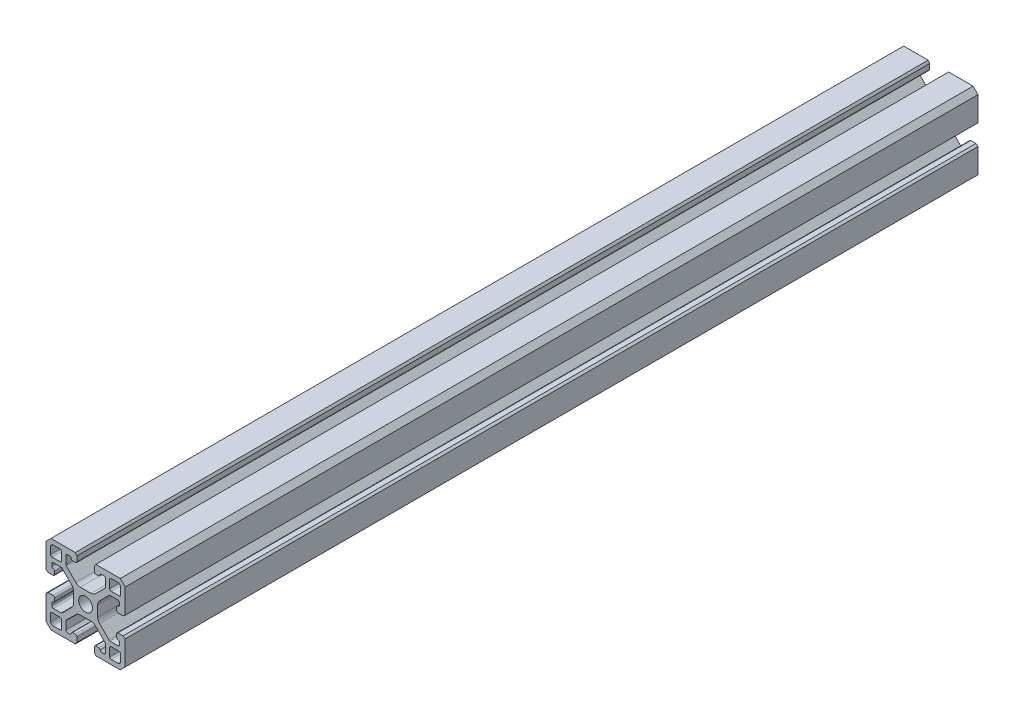
SolidWorks part; units mm, degrees
material "6063-T6"
ref_plane "Front Plane" through (0, 0, 0) normal (0, 0, 1) x (1, 0, 0)
ref_plane "Top Plane" through (0, 0, 0) normal (0, 1, 0) x (1, 0, 0)
ref_plane "Right Plane" through (0, 0, 0) normal (1, 0, 0) x (0, 0, -1)
sketch "Sketch1" plane through (0, 0, 0) normal (0, 0, 1) x (-1, 0, 0)
  line L0 (19.05, 0) -> (-19.05, 0) construction
  line L1 (0, -19.05) -> (0, 19.05) construction
  line L2 (-19.05, 4.9276) -> (-19.05, 16.6878)
  line L3 (-18.044, 4.1656) -> (-19.05, 4.9276)
  line L4 (-15.6692, 4.1656) -> (-18.044, 4.1656)
  line L5 (-14.9297, 6.2238) -> (-14.9074, 4.9409)
  line L6 (-16.256, 8.763) -> (-16.256, 7.7216)
  line L7 (-16.256, -7.7216) -> (-16.256, -8.763)
  line L8 (-14.9074, -4.9409) -> (-14.9297, -6.2238)
  line L9 (-18.044, -4.1656) -> (-15.6692, -4.1656)
  line L10 (-19.05, -4.9276) -> (-18.044, -4.1656)
  line L11 (-19.05, -16.6878) -> (-19.05, -4.9276)
  line L26 (-16.8656, 12.319) -> (-16.8656, 15.6829)
  line L27 (-16.6424, 16.2217) -> (-16.2217, 16.6424)
  line L28 (-15.6829, 16.8656) -> (-12.319, 16.8656)
  line L29 (-11.557, 16.1036) -> (-11.557, 12.319)
  line L30 (-12.319, 11.557) -> (-16.1036, 11.557)
  line L31 (-6.7001, -4.7245) -> (-11.2775, -9.3018)
  line L32 (-11.8163, -9.525) -> (-15.494, -9.525)
  line L34 (-15.494, 9.525) -> (-11.8163, 9.525)
  line L35 (-11.2775, 9.3018) -> (-6.7001, 4.7245)
  line L36 (-5.8074, 2.5692) -> (-5.8074, -2.5692)
  line L37 (-16.1036, -11.557) -> (-12.319, -11.557)
  line L38 (-11.557, -12.319) -> (-11.557, -16.1036)
  line L39 (-12.319, -16.8656) -> (-15.6829, -16.8656)
  line L40 (-16.2217, -16.6424) -> (-16.6424, -16.2217)
  line L41 (-16.8656, -15.6829) -> (-16.8656, -12.319)
  line L42 (15.6829, -16.8656) -> (12.319, -16.8656)
  line L43 (11.557, -16.1036) -> (11.557, -12.319)
  line L44 (12.319, -11.557) -> (16.1036, -11.557)
  line L45 (16.8656, -12.319) -> (16.8656, -15.6829)
  line L46 (16.6424, -16.2217) -> (16.2217, -16.6424)
  line L47 (11.557, 12.319) -> (11.557, 16.1036)
  line L48 (12.319, 16.8656) -> (15.6829, 16.8656)
  line L49 (16.2217, 16.6424) -> (16.6424, 16.2217)
  line L100 (5.8074, -2.5692) -> (5.8074, 2.5692)
  line L101 (6.7001, 4.7245) -> (11.2775, 9.3018)
  line L102 (11.8163, 9.525) -> (15.494, 9.525)
  line L103 (16.256, 8.763) -> (16.256, 7.7216)
  line L104 (14.9297, 6.2238) -> (14.9074, 4.9409)
  line L105 (15.6692, 4.1656) -> (18.044, 4.1656)
  line L106 (18.044, 4.1656) -> (19.05, 4.9276)
  line L107 (19.05, 4.9276) -> (19.05, 16.6878)
  line L108 (19.05, 16.6878) -> (16.6878, 19.05)
  line L109 (16.6878, 19.05) -> (4.9276, 19.05)
  line L110 (4.9276, 19.05) -> (4.1656, 18.044)
  line L111 (4.1656, 18.044) -> (4.1656, 15.6692)
  line L112 (4.9409, 14.9074) -> (6.2238, 14.9297)
  line L113 (7.7216, 16.256) -> (8.763, 16.256)
  line L114 (9.525, 15.494) -> (9.525, 11.8163)
  line L115 (9.3018, 11.2775) -> (4.7245, 6.7001)
  line L116 (2.5692, 5.8074) -> (-2.5692, 5.8074)
  line L117 (-4.7245, 6.7001) -> (-9.3018, 11.2775)
  line L118 (-9.525, 11.8163) -> (-9.525, 15.494)
  line L119 (-8.763, 16.256) -> (-7.7216, 16.256)
  line L120 (-6.2238, 14.9297) -> (-4.9409, 14.9074)
  line L121 (-4.1656, 15.6692) -> (-4.1656, 18.044)
  line L122 (-4.1656, 18.044) -> (-4.9276, 19.05)
  line L123 (-4.9276, 19.05) -> (-16.6878, 19.05)
  line L124 (-16.6878, 19.05) -> (-19.05, 16.6878)
  line L126 (-19.05, -16.6878) -> (-16.6878, -19.05)
  line L127 (-16.6878, -19.05) -> (-4.9276, -19.05)
  line L128 (-4.9276, -19.05) -> (-4.1656, -18.044)
  line L129 (-4.1656, -18.044) -> (-4.1656, -15.6692)
  line L130 (-4.9409, -14.9074) -> (-6.2238, -14.9297)
  line L131 (-7.7216, -16.256) -> (-8.763, -16.256)
  line L132 (-9.525, -15.494) -> (-9.525, -11.8163)
  line L133 (-9.3018, -11.2775) -> (-4.7245, -6.7001)
  line L134 (-2.5692, -5.8074) -> (2.5692, -5.8074)
  line L135 (4.7245, -6.7001) -> (9.3018, -11.2775)
  line L136 (9.525, -11.8163) -> (9.525, -15.494)
  line L137 (8.763, -16.256) -> (7.7216, -16.256)
  line L138 (6.2238, -14.9297) -> (4.9409, -14.9074)
  line L139 (4.1656, -15.6692) -> (4.1656, -18.044)
  line L140 (4.1656, -18.044) -> (4.9409, -19.05)
  line L141 (4.9409, -19.05) -> (16.6878, -19.05)
  line L142 (16.6878, -19.05) -> (19.05, -16.6878)
  line L143 (19.05, -16.6878) -> (19.05, -4.9276)
  line L144 (19.05, -4.9276) -> (18.044, -4.1656)
  line L145 (18.044, -4.1656) -> (15.6692, -4.1656)
  line L146 (14.9074, -4.9409) -> (14.9297, -6.2238)
  line L147 (16.256, -7.7216) -> (16.256, -8.763)
  line L148 (15.494, -9.525) -> (11.8163, -9.525)
  line L149 (11.2775, -9.3018) -> (6.7001, -4.7245)
  line L150 (16.8656, 15.6829) -> (16.8656, 12.319)
  line L151 (16.1036, 11.557) -> (12.319, 11.557)
  arc A0 (-16.256, 8.763) -> (-15.494, 9.525) centre (-15.494, 8.763) cw
  arc A1 (-14.9074, 4.9409) -> (-15.6692, 4.1656) centre (-15.6692, 4.9276) cw
  arc A2 (-15.5928, 6.966) -> (-14.9297, 6.2238) centre (-15.6916, 6.2105) cw
  arc A3 (-15.5928, 6.966) -> (-16.256, 7.7216) centre (-15.494, 7.7216) cw
  arc A4 (-15.494, -9.525) -> (-16.256, -8.763) centre (-15.494, -8.763) cw
  arc A5 (-16.256, -7.7216) -> (-15.5928, -6.966) centre (-15.494, -7.7216) cw
  arc A6 (-14.9297, -6.2238) -> (-15.5928, -6.966) centre (-15.6916, -6.2105) cw
  arc A7 (-15.6692, -4.1656) -> (-14.9074, -4.9409) centre (-15.6692, -4.9276) cw
  arc A27 (-16.6424, 16.2217) -> (-16.8656, 15.6829) centre (-16.1036, 15.6829) ccw
  arc A28 (-15.6829, 16.8656) -> (-16.2217, 16.6424) centre (-15.6829, 16.1036) ccw
  arc A29 (-11.557, 16.1036) -> (-12.319, 16.8656) centre (-12.319, 16.1036) ccw
  arc A30 (-12.319, 11.557) -> (-11.557, 12.319) centre (-12.319, 12.319) ccw
  arc A31 (-16.8656, 12.319) -> (-16.1036, 11.557) centre (-16.1036, 12.319) ccw
  arc A32 (-11.8163, -9.525) -> (-11.2775, -9.3018) centre (-11.8163, -8.763) ccw
  arc A35 (-11.2775, 9.3018) -> (-11.8163, 9.525) centre (-11.8163, 8.763) ccw
  arc A72 (5.8074, -2.5692) -> (6.7001, -4.7245) centre (8.8554, -2.5692) ccw
  arc A73 (6.7001, 4.7245) -> (5.8074, 2.5692) centre (8.8554, 2.5692) ccw
  arc A74 (11.8163, 9.525) -> (11.2775, 9.3018) centre (11.8163, 8.763) ccw
  arc A75 (16.256, 8.763) -> (15.494, 9.525) centre (15.494, 8.763) ccw
  arc A76 (15.5928, 6.966) -> (16.256, 7.7216) centre (15.494, 7.7216) ccw
  arc A77 (15.5928, 6.966) -> (14.9297, 6.2238) centre (15.6916, 6.2105) ccw
  arc A78 (14.9074, 4.9409) -> (15.6692, 4.1656) centre (15.6692, 4.9276) ccw
  arc A79 (4.1656, 15.6692) -> (4.9409, 14.9074) centre (4.9276, 15.6692) ccw
  arc A80 (6.2238, 14.9297) -> (6.966, 15.5928) centre (6.2105, 15.6916) ccw
  arc A81 (7.7216, 16.256) -> (6.966, 15.5928) centre (7.7216, 15.494) ccw
  arc A82 (9.525, 15.494) -> (8.763, 16.256) centre (8.763, 15.494) ccw
  arc A83 (9.3018, 11.2775) -> (9.525, 11.8163) centre (8.763, 11.8163) ccw
  arc A84 (2.5692, 5.8074) -> (4.7245, 6.7001) centre (2.5692, 8.8554) ccw
  arc A85 (-4.7245, 6.7001) -> (-2.5692, 5.8074) centre (-2.5692, 8.8554) ccw
  arc A86 (-9.525, 11.8163) -> (-9.3018, 11.2775) centre (-8.763, 11.8163) ccw
  arc A87 (-8.763, 16.256) -> (-9.525, 15.494) centre (-8.763, 15.494) ccw
  arc A88 (-6.966, 15.5928) -> (-7.7216, 16.256) centre (-7.7216, 15.494) ccw
  arc A89 (-6.966, 15.5928) -> (-6.2238, 14.9297) centre (-6.2105, 15.6916) ccw
  arc A90 (-4.9409, 14.9074) -> (-4.1656, 15.6692) centre (-4.9276, 15.6692) ccw
  arc A91 (-4.1656, -15.6692) -> (-4.9409, -14.9074) centre (-4.9276, -15.6692) ccw
  arc A92 (-6.2238, -14.9297) -> (-6.966, -15.5928) centre (-6.2105, -15.6916) ccw
  arc A93 (-7.7216, -16.256) -> (-6.966, -15.5928) centre (-7.7216, -15.494) ccw
  arc A94 (-9.525, -15.494) -> (-8.763, -16.256) centre (-8.763, -15.494) ccw
  arc A95 (-9.3018, -11.2775) -> (-9.525, -11.8163) centre (-8.763, -11.8163) ccw
  arc A96 (-2.5692, -5.8074) -> (-4.7245, -6.7001) centre (-2.5692, -8.8554) ccw
  arc A97 (4.7245, -6.7001) -> (2.5692, -5.8074) centre (2.5692, -8.8554) ccw
  arc A98 (9.525, -11.8163) -> (9.3018, -11.2775) centre (8.763, -11.8163) ccw
  arc A99 (8.763, -16.256) -> (9.525, -15.494) centre (8.763, -15.494) ccw
  arc A100 (6.966, -15.5928) -> (7.7216, -16.256) centre (7.7216, -15.494) ccw
  arc A101 (6.966, -15.5928) -> (6.2238, -14.9297) centre (6.2105, -15.6916) ccw
  arc A102 (4.9409, -14.9074) -> (4.1656, -15.6692) centre (4.9276, -15.6692) ccw
  arc A103 (15.6692, -4.1656) -> (14.9074, -4.9409) centre (15.6692, -4.9276) ccw
  arc A104 (14.9297, -6.2238) -> (15.5928, -6.966) centre (15.6916, -6.2105) ccw
  arc A105 (16.256, -7.7216) -> (15.5928, -6.966) centre (15.494, -7.7216) ccw
  arc A106 (15.494, -9.525) -> (16.256, -8.763) centre (15.494, -8.763) ccw
  arc A107 (11.2775, -9.3018) -> (11.8163, -9.525) centre (11.8163, -8.763) ccw
  arc A108 (-5.8074, 2.5692) -> (-6.7001, 4.7245) centre (-8.8554, 2.5692) ccw
  arc A109 (-6.7001, -4.7245) -> (-5.8074, -2.5692) centre (-8.8554, -2.5692) ccw
  arc A110 (-11.557, -12.319) -> (-12.319, -11.557) centre (-12.319, -12.319) ccw
  arc A111 (-12.319, -16.8656) -> (-11.557, -16.1036) centre (-12.319, -16.1036) ccw
  arc A112 (-16.2217, -16.6424) -> (-15.6829, -16.8656) centre (-15.6829, -16.1036) ccw
  arc A113 (-16.8656, -15.6829) -> (-16.6424, -16.2217) centre (-16.1036, -15.6829) ccw
  arc A114 (-16.1036, -11.557) -> (-16.8656, -12.319) centre (-16.1036, -12.319) ccw
  circle A115 centre (0, 0) radius 3.3147
  arc A116 (11.557, -16.1036) -> (12.319, -16.8656) centre (12.319, -16.1036) ccw
  arc A117 (12.319, -11.557) -> (11.557, -12.319) centre (12.319, -12.319) ccw
  arc A118 (16.8656, -12.319) -> (16.1036, -11.557) centre (16.1036, -12.319) ccw
  arc A119 (16.6424, -16.2217) -> (16.8656, -15.6829) centre (16.1036, -15.6829) ccw
  arc A120 (15.6829, -16.8656) -> (16.2217, -16.6424) centre (15.6829, -16.1036) ccw
  arc A121 (12.319, 16.8656) -> (11.557, 16.1036) centre (12.319, 16.1036) ccw
  arc A122 (16.2217, 16.6424) -> (15.6829, 16.8656) centre (15.6829, 16.1036) ccw
  arc A123 (16.8656, 15.6829) -> (16.6424, 16.2217) centre (16.1036, 15.6829) ccw
  arc A124 (16.1036, 11.557) -> (16.8656, 12.319) centre (16.1036, 12.319) ccw
  arc A125 (11.557, 12.319) -> (12.319, 11.557) centre (12.319, 12.319) ccw
  dimension "D1" = 6.6294
  dimension "D2" = 38.1
  dimension "D3" = 38.1
extrude "Boss-Extrude1" add sketch "Sketch1" along normal blind 410.21
